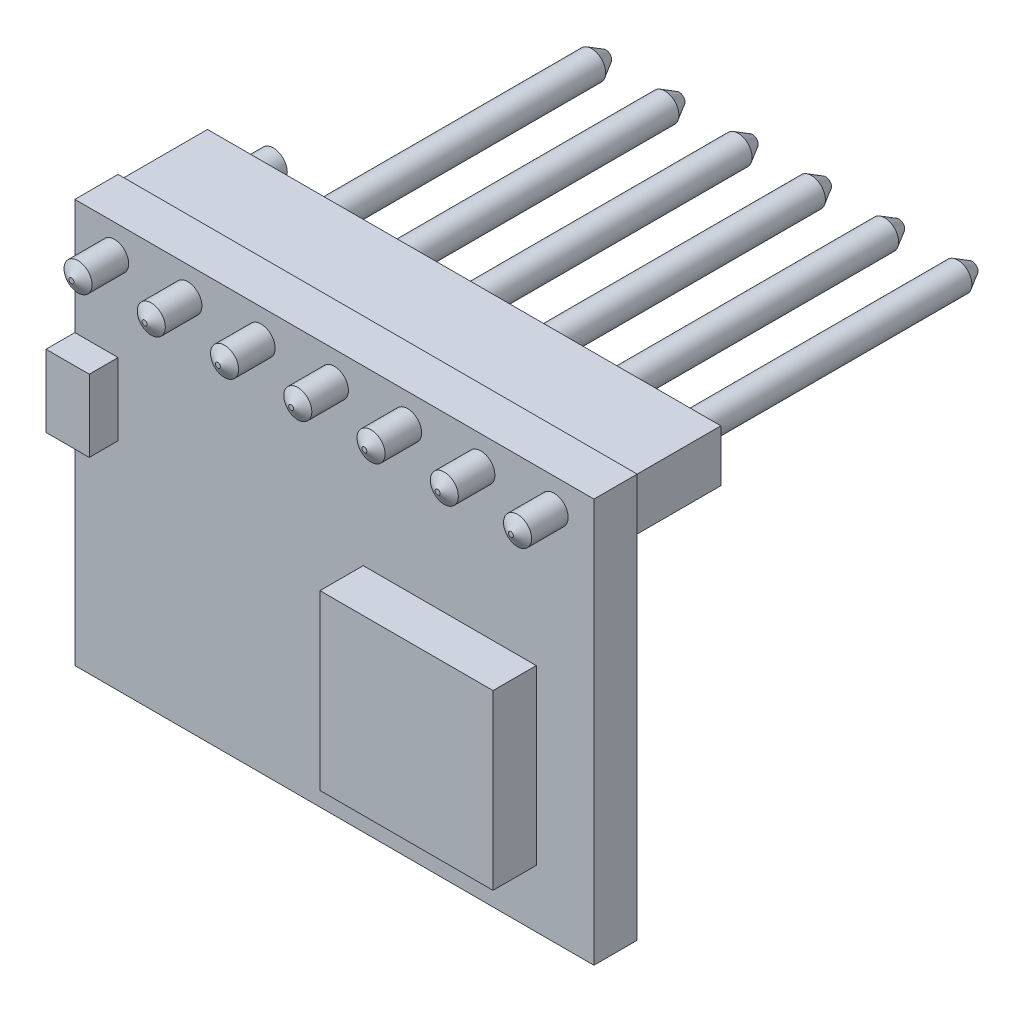
SolidWorks part; units mm, degrees
ref_plane "Plan de face" through (0, 0, 0) normal (0, 0, 1) x (1, 0, 0)
ref_plane "Plan de dessus" through (0, 0, 0) normal (0, 1, 0) x (1, 0, 0)
ref_plane "Plan de droite" through (0, 0, 0) normal (1, 0, 0) x (0, 0, -1)
sketch "Esquisse1" plane through (0, 0, 0) normal (0, 0, 1) x (1, 0, 0)
  line L1 (0, 0) -> (18, 0)
  line L2 (0, 0) -> (0, 14)
  line L3 (0, 14) -> (18, 14)
  line L4 (18, 0) -> (18, 14)
extrude "Boss.-Extru.1" add sketch "Esquisse1" along normal blind 1.5
sketch "Esquisse4" plane through (0, 0, 1.5) normal (0, 0, 1) x (1, 0, 0)
  line L0 (0, 14) -> (0, 0) construction
  line L1 (0, 10) -> (1.5, 10)
  line L2 (0, 10) -> (0, 7.5)
  line L3 (0, 7.5) -> (1.5, 7.5)
  line L4 (1.5, 10) -> (1.5, 7.5)
  line L5 (18, 14) -> (0, 14) construction
  dimension "D1" = 2.5
  dimension "D2" = 1.5
  dimension "D3" = 4
extrude "Boss.-Extru.4" add sketch "Esquisse4" along normal blind 1
sketch "Esquisse5" plane through (0, 0, 0) normal (0, 0, -1) x (-1, 0, 0)
  line L2 (-17.9, 13.9) -> (-0.1, 13.9)
  line L3 (-17.9, 13.9) -> (-17.9, 12.1)
  line L4 (-17.9, 12.1) -> (-0.1, 12.1)
  line L5 (-0.1, 13.9) -> (-0.1, 12.1)
  line L7 (-18, 14) -> (0, 14) construction
  line L10 (0, 14) -> (0, 0) construction
  dimension "D1" = 0.1
  dimension "D2" = 0.1
  dimension "D3" = 17.8
  dimension "D4" = 1.8
extrude "Boss.-Extru.5" add sketch "Esquisse5" along normal blind 3
sketch "Esquisse6" plane through (0, 0, -3) normal (0, 0, -1) x (-1, 0, 0)
  line L0 (-0.1, 13.9) -> (-17.9, 13.9) construction
  line L2 (-0.1, 12.1) -> (-0.1, 13.9) construction
  circle A0 centre (-1.38, 13) radius 0.4862
  circle A1 centre (-3.92, 13) radius 0.4862
  circle A2 centre (-6.46, 13) radius 0.4862
  circle A3 centre (-9, 13) radius 0.4862
  circle A4 centre (-11.54, 13) radius 0.4862
  circle A5 centre (-14.08, 13) radius 0.4862
  circle A6 centre (-16.62, 13) radius 0.4862
  dimension "D1" = 0.9
  dimension "D2" = 1.28
  dimension "D3" = 7
extrude "Boss.-Extru.6" add sketch "Esquisse6" along normal blind 10 and the other way blind 6
chamfer "Chanfrein2" distance 0.5 angle 30 7 edges at (16.1338, 13, -13) (13.5938, 13, -13) (11.0538, 13, -13) (8.5138, 13, -13) (5.9738, 13, -13) (3.4338, 13, -13) (0.8938, 13, -13)
sketch "Esquisse7" plane through (0, 13.9, 0) normal (0, 1, 0) x (1, 0, 0)
  line L0 (0.1, 3) -> (17.9, 3) construction
  line L1 (0, 13.3176) -> (2.5, 13.3176)
  line L2 (0, 13.3176) -> (0, 4)
  line L3 (0, 4) -> (2.5, 4)
  line L4 (2.5, 13.3176) -> (2.5, 4)
  dimension "D1" = 1
extrude "Enlèv. mat.-Extru.1" cut sketch "Esquisse7" against normal through all
chamfer "Chanfrein3" distance 0.4 angle 30 7 edges at (0.8938, 13, 3) (16.1338, 13, 3) (13.5938, 13, 3) (11.0538, 13, 3) (8.5138, 13, 3) (5.9738, 13, 3) (3.4338, 13, 3)
sketch "Esquisse8" plane through (0, 0, 1.5) normal (0, 0, 1) x (1, 0, 0)
  line L0 (18, 0) -> (18, 14) construction
  line L1 (10, 8) -> (16, 8)
  line L2 (10, 8) -> (10, 2)
  line L3 (10, 2) -> (16, 2)
  line L4 (16, 8) -> (16, 2)
  line L5 (0, 0) -> (18, 0) construction
  dimension "D1" = 2
  dimension "D2" = 6
  dimension "D3" = 2
  dimension "D4" = 6
extrude "Boss.-Extru.7" add sketch "Esquisse8" along normal blind 1.5
